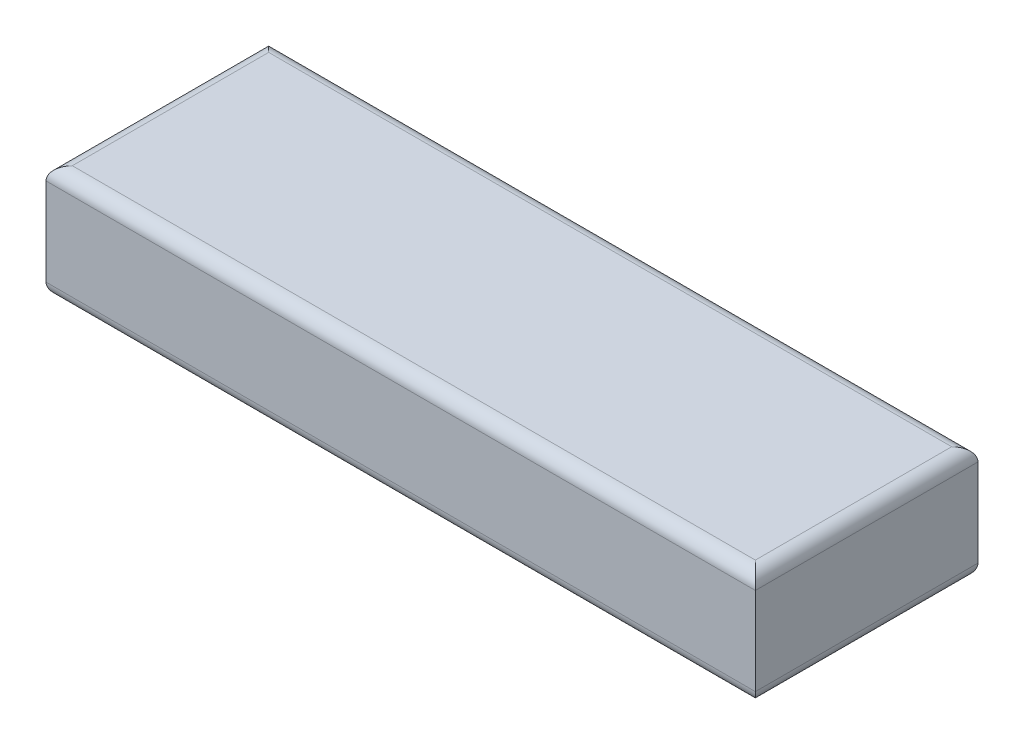
SolidWorks part; units mm, degrees
ref_plane "Front Plane" through (0, 0, 0) normal (0, 0, 1) x (1, 0, 0)
ref_plane "Top Plane" through (0, 0, 0) normal (0, 1, 0) x (1, 0, 0)
ref_plane "Right Plane" through (0, 0, 0) normal (1, 0, 0) x (0, 0, -1)
sketch "Sketch1" plane through (0, 0, 0) normal (0, 1, 0) x (1, 0, 0)
  line L1 (-2.7063, -52.4148) -> (134.2937, -52.4148)
  line L2 (-2.7063, -52.4148) -> (-2.7063, -9.4148)
  line L3 (-2.7063, -9.4148) -> (134.2937, -9.4148)
  line L4 (134.2937, -52.4148) -> (134.2937, -9.4148)
  dimension "D1" = 43
  dimension "D2" = 137
extrude "Boss-Extrude1" add sketch "Sketch1" along normal blind 22
fillet "Fillet1" radius 2.54 8 edges at (65.7937, 0, 9.4148) (134.2937, 0, 30.9148) (65.7937, 0, 52.4148) (-2.7063, 0, 30.9148) (65.7937, 22, 52.4148) (134.2937, 22, 30.9148) (65.7937, 22, 9.4148) (-2.7063, 22, 30.9148)
